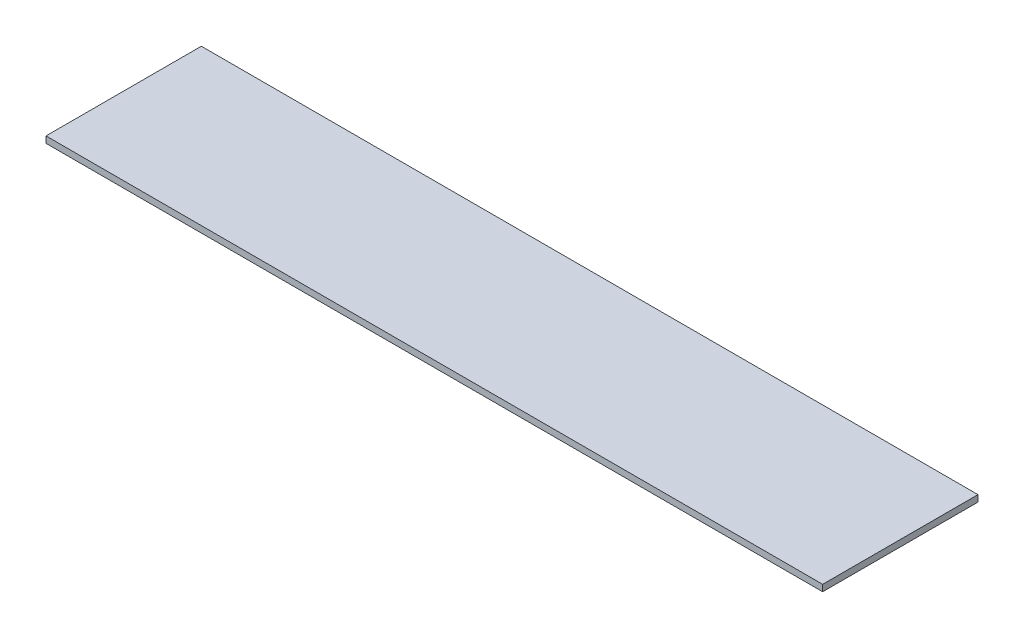
SolidWorks part; units mm, degrees
material "1060 Alloy"
ref_plane "Front Plane" through (0, 0, 0) normal (0, 0, 1) x (1, 0, 0)
ref_plane "Top Plane" through (0, 0, 0) normal (0, 1, 0) x (1, 0, 0)
ref_plane "Right Plane" through (0, 0, 0) normal (1, 0, 0) x (0, 0, -1)
sketch "Sketch1" plane through (0, 0, 0) normal (0, 1, 0) x (1, 0, 0)
  line L1 (0, 0) -> (-1524, 0)
  line L2 (0, 0) -> (0, 304.8)
  line L3 (0, 304.8) -> (-1524, 304.8)
  line L4 (-1524, 0) -> (-1524, 304.8)
  dimension "D1" = 1524
  dimension "D2" = 304.8
extrude "Boss-Extrude1" add sketch "Sketch1" along normal blind 12.7 contours L1 L4 L3 L2
